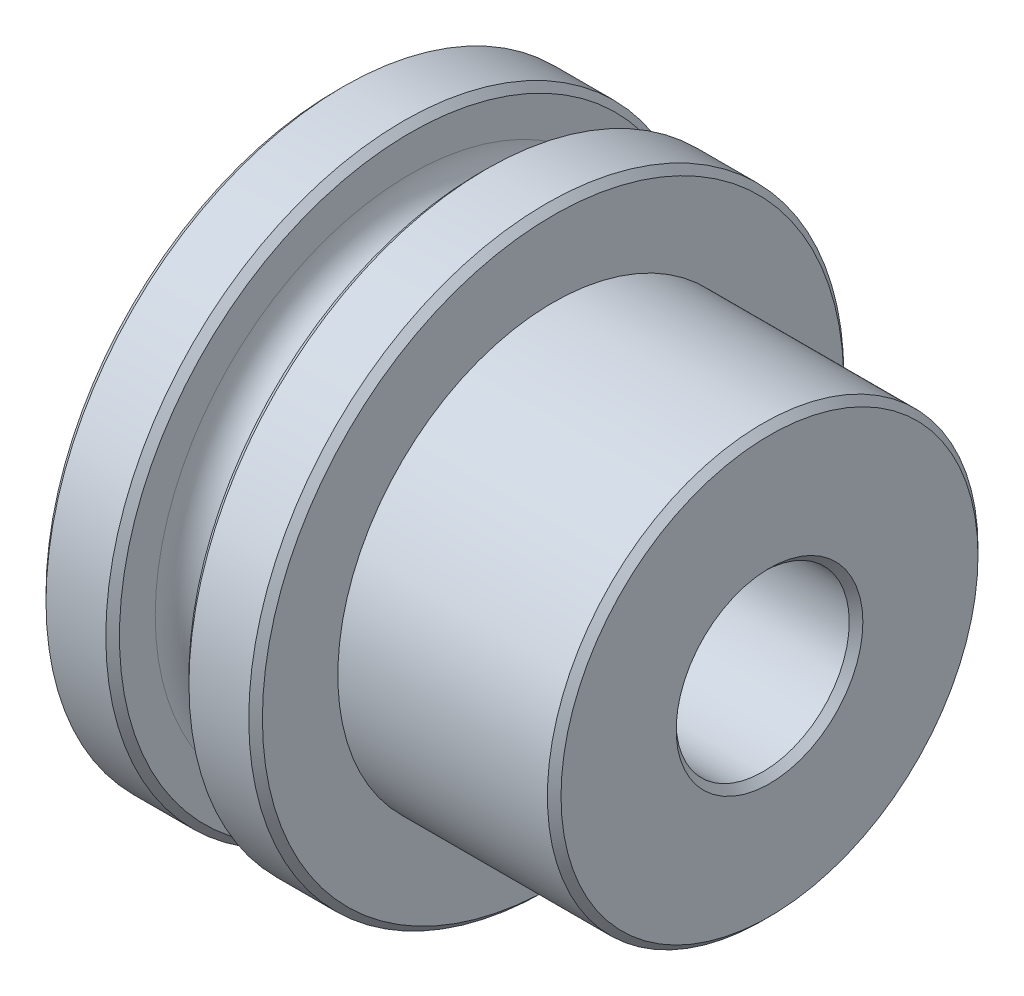
SolidWorks part; units mm, degrees
material "Nylon 101"
ref_plane "Front Plane" through (0, 0, 0) normal (0, 0, 1) x (1, 0, 0)
ref_plane "Top Plane" through (0, 0, 0) normal (0, 1, 0) x (1, 0, 0)
ref_plane "Right Plane" through (0, 0, 0) normal (1, 0, 0) x (0, 0, -1)
sketch "Sketch1" plane through (0, 0, 0) normal (1, 0, 0) x (0, 0, -1)
  circle A0 centre (0, 0) radius 12.6365
  dimension "D1" = 25.273
extrude "Boss-Extrude1" add sketch "Sketch1" along normal blind 12.7
sketch "Sketch2" plane through (0, 0, 0) normal (-1, 0, 0) x (0, 0, 1)
  circle A0 centre (0, 0) radius 17.4625
  dimension "D1" = 34.925
extrude "Boss-Extrude2" add sketch "Sketch2" along normal blind 12.7
sketch "Sketch3" plane through (-12.7, 0, 0) normal (-1, 0, 0) x (0, 0, 1)
  circle A0 centre (0, 0) radius 11.1125
  dimension "D1" = 22.225
extrude "Cut-Extrude1" cut sketch "Sketch3" against normal blind 7.112
sketch "Sketch4" plane through (-5.588, 0, 0) normal (-1, 0, 0) x (0, 0, 1)
  circle A0 centre (0, 0) radius 7.2746
  dimension "D1" = 14.5492
extrude "Cut-Extrude2" cut sketch "Sketch4" against normal blind 0.2
sketch "Sketch5" plane through (-5.388, 0, 0) normal (-1, 0, 0) x (0, 0, 1)
  circle A0 centre (0, 0) radius 5.08
  dimension "D1" = 10.16
extrude "Cut-Extrude3" cut sketch "Sketch5" against normal through all
sketch "Sketch6" plane through (0, 0, 0) normal (0, 0, 1) x (1, 0, 0)
  line L0 (-8.39, 17.4625) -> (-8.39, 14.9625)
  line L1 (0, 17.4625) -> (-12.7, 17.4625) construction
  line L2 (-4.31, 17.4625) -> (-4.31, 14.9625)
  line L3 (-6.35, 12.9225) -> (-6.35, 0) construction
  line L4 (-6.35, 14.9625) -> (-6.35, 17.4625) construction
  line L5 (-8.39, 17.4625) -> (-4.31, 17.4625)
  line L6 (-8.39, 17.4625) -> (-4.31, 17.4625)
  line L7 (-6.35, 0) -> (0, 0) construction
  line L8 (0, -17.4625) -> (0, 17.4625) construction
  arc A0 (-8.39, 14.9625) -> (-4.31, 14.9625) centre (-6.35, 14.9625) ccw
  dimension "D1" = 2.04
  dimension "D2" = 12.9225
  dimension "D3" = 2.5
  dimension "D4" = 6.35
revolve "Cut-Revolve1" cut sketch "Sketch6" angle 360 about L7
chamfer "Chamfer1" distance 0.4 angle 45 7 edges at (12.7, 0, -12.6365) (12.7, 0, 5.08) (-12.7, 0, 17.4625) (-12.7, 0, 11.1125) (-8.39, 0, 17.4625) (0, 0, 17.4625) (-4.31, 0, 17.4625)
equation "\"D1@Sketch6\"=2mm+.04mm"
equation "\"D2@Sketch6\"=19mm/2"
equation "\"D3@Sketch6\"=2.5mm"
